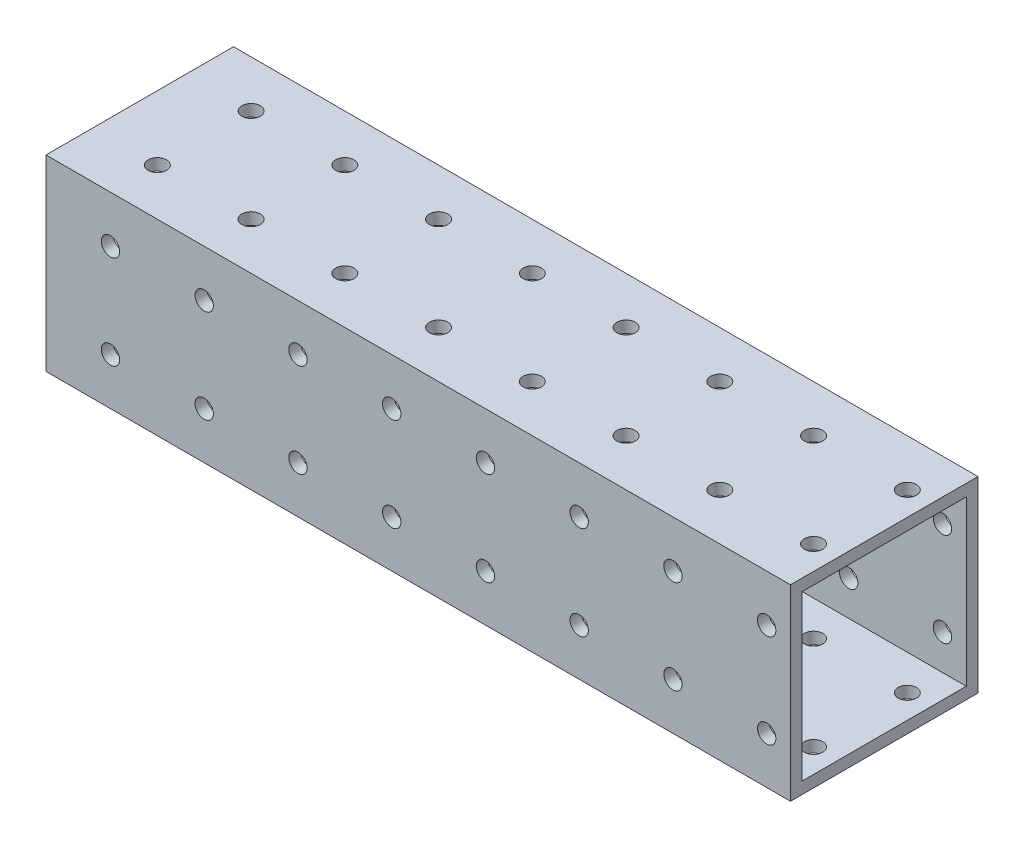
SolidWorks part; units mm, degrees
material "6061-T6 (SS)"
ref_plane "Front Plane" through (0, 0, 0) normal (0, 0, 1) x (1, 0, 0)
ref_plane "Top Plane" through (0, 0, 0) normal (0, 1, 0) x (1, 0, 0)
ref_plane "Right Plane" through (0, 0, 0) normal (1, 0, 0) x (0, 0, -1)
sketch "Sketch1" plane through (0, 0, 0) normal (1, 0, 0) x (0, 0, -1)
  line L1 (0, 0) -> (50.8, 0)
  line L2 (0, 0) -> (0, 50.8)
  line L3 (0, 50.8) -> (50.8, 50.8)
  line L4 (50.8, 0) -> (50.8, 50.8)
  dimension "D1" = 50.8
extrude "Boss-Extrude1" add sketch "Sketch1" along normal blind 201.7201
shell "Shell1" thickness 3.175
sketch "Sketch2" plane through (0, 0, -50.8) normal (0, 0, -1) x (-1, 0, 0)
  line L0 (-195.2625, 0) -> (-195.2625, 50.8) construction
  line L1 (-201.7201, 0) -> (0, 0) construction
  line L2 (-201.7201, 50.8) -> (0, 50.8) construction
  line L3 (-201.7201, 0) -> (-201.7201, 50.8) construction
  circle A22 centre (-195.2625, 38.1) radius 2.4892
  circle A23 centre (-195.2625, 12.7) radius 2.4892
  dimension "D2" = 4.9784
  dimension "D3" = 25.4
  dimension "D4" = 12.7
  dimension "D1" = 6.4576
extrude "Cut-Extrude3" cut sketch "Sketch2" against normal through all contours A23
sketch "Sketch3" plane through (0, 0, 0) normal (0, -1, 0) x (1, 0, 0)
  line L0 (195.2625, 0) -> (195.2625, -50.8) construction
  line L1 (201.7201, 0) -> (0, 0) construction
  line L2 (201.7201, -50.8) -> (0, -50.8) construction
  line L5 (201.7201, -50.8) -> (201.7201, 0) construction
  circle A2 centre (195.2625, -12.7) radius 2.4892
  circle A3 centre (195.2625, -38.1) radius 2.4892
  dimension "D1" = 4.9784
  dimension "D2" = 12.7
  dimension "D3" = 25.4
  dimension "D4" = 6.4576
extrude "Cut-Extrude2" cut sketch "Sketch3" against normal through all
pattern_linear "LPattern1" count 8 spacing 25.4 along (-1, 0, 0) of "Cut-Extrude2", "Cut-Extrude3"
